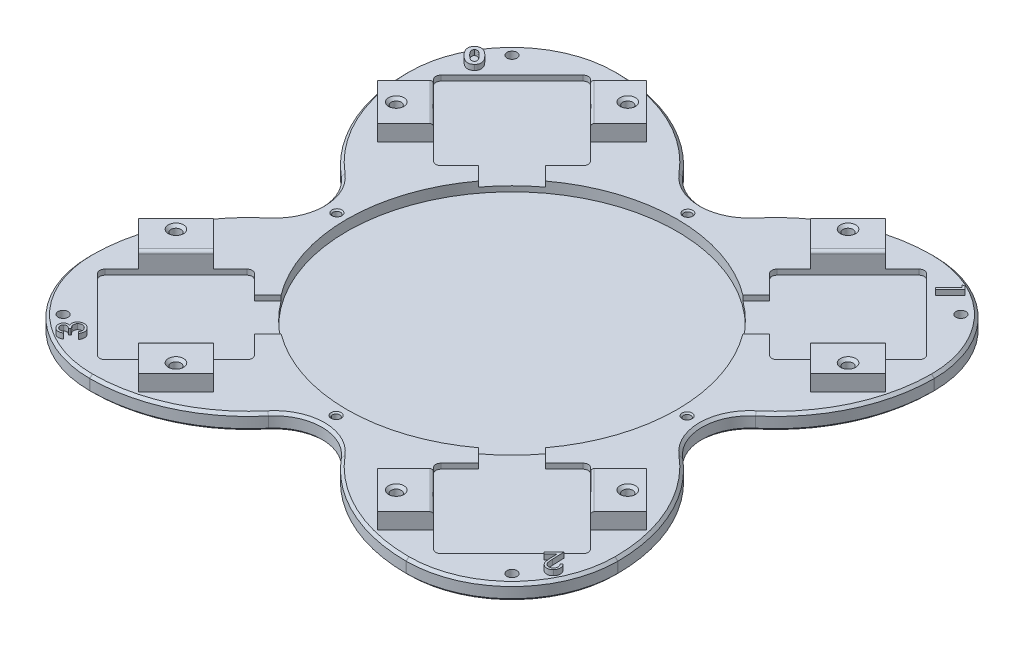
SolidWorks part; units mm, degrees
ref_plane "Спереди" through (0, 0, 0) normal (0, 0, 1) x (1, 0, 0)
ref_plane "Сверху" through (0, 0, 0) normal (0, 1, 0) x (1, 0, 0)
ref_plane "Справа" through (0, 0, 0) normal (1, 0, 0) x (0, 0, -1)
sketch "Эскиз1" plane through (0, 0, 0) normal (0, 1, 0) x (1, 0, 0)
  line L1 (-100, -100) -> (100, -100)
  line L2 (-100, -100) -> (-100, 100)
  line L3 (-100, 100) -> (100, 100)
  line L4 (100, -100) -> (100, 100)
  line L5 (0, 100) -> (0, -100) construction
  line L6 (-100, 0) -> (100, 0) construction
  line L11 (0, 75) -> (0, -75) construction
  line L12 (-39.5, 0) -> (39.5, 0) construction
  line L13 (-85, -85) -> (85, -85) construction
  line L14 (-85, -85) -> (-85, 85) construction
  line L15 (-85, 85) -> (85, 85) construction
  line L16 (85, -85) -> (85, 85) construction
  line L17 (0, 85) -> (0, -85) construction
  line L18 (-85, 0) -> (85, 0) construction
  circle A8 centre (-90, 0) radius 1.9
  circle A9 centre (0, 90) radius 1.9
  circle A10 centre (90, 0) radius 1.9
  circle A11 centre (0, -90) radius 1.9
  circle A12 centre (-85, 85) radius 1.9
  circle A13 centre (85, 85) radius 1.9
  circle A14 centre (85, -85) radius 1.9
  circle A15 centre (-85, -85) radius 1.9
  point P0 (0, 0)
  point P4 (0, 0)
  point P11 (0, 0)
  point P27 (0, 0)
  dimension "D6" = 90
  dimension "D2" = 3.8
  dimension "D1" = 200
  dimension "D8" = 170
  dimension "D7" = 4
extrude "Бобышка-Вытянуть1" add sketch "Эскиз1" along normal blind 6
sketch "Эскиз2" plane through (0, 6, 0) normal (0, 1, 0) x (1, 0, 0)
  line L0 (0, 72.2532) -> (0, 0) construction
  line L1 (0, 0) -> (100, 100) construction
  line L2 (63.6396, 33.9411) -> (33.9411, 63.6396)
  line L3 (63.6396, 33.9411) -> (93.3381, 63.6396)
  line L4 (33.9411, 63.6396) -> (63.6396, 93.3381)
  line L5 (93.3381, 63.6396) -> (63.6396, 93.3381)
  line L6 (63.6396, 33.9411) -> (63.6396, 93.3381) construction
  line L7 (33.9411, 63.6396) -> (93.3381, 63.6396) construction
  line L8 (33.9411, -63.6396) -> (63.6396, -33.9411)
  line L9 (33.9411, -63.6396) -> (63.6396, -93.3381)
  line L10 (63.6396, -93.3381) -> (93.3381, -63.6396)
  line L11 (63.6396, -33.9411) -> (93.3381, -63.6396)
  line L12 (-63.6396, -33.9411) -> (-33.9411, -63.6396)
  line L13 (-63.6396, -33.9411) -> (-93.3381, -63.6396)
  line L14 (-93.3381, -63.6396) -> (-63.6396, -93.3381)
  line L15 (-33.9411, -63.6396) -> (-63.6396, -93.3381)
  line L16 (-33.9411, 63.6396) -> (-63.6396, 33.9411)
  line L17 (-33.9411, 63.6396) -> (-63.6396, 93.3381)
  line L18 (-63.6396, 93.3381) -> (-93.3381, 63.6396)
  line L19 (-63.6396, 33.9411) -> (-93.3381, 63.6396)
  line L20 (0, 0) -> (119.0497, 0) construction
  point P6 (63.6396, 63.6396)
  point P24 (0, 0)
  dimension "D1" = 42
  dimension "D2" = 90
  dimension "D4" = 63.6396
  dimension "D5" = 63.6396
  dimension "D3" = 4
extrude "Вырез-Вытянуть1" cut sketch "Эскиз2" against normal blind 2
fillet "Скругление1" radius 2 16 edges at (63.6396, 5, -33.9411) (33.9411, 5, -63.6396) (93.3381, 5, -63.6396) (63.6396, 5, -93.3381) (-63.6396, 5, -93.3381) (-63.6396, 5, -33.9411) (-93.3381, 5, -63.6396) (-33.9411, 5, -63.6396) (63.6396, 5, 93.3381) (93.3381, 5, 63.6396) (63.6396, 5, 33.9411) (33.9411, 5, 63.6396) (-63.6396, 5, 93.3381) (-33.9411, 5, 63.6396) (-63.6396, 5, 33.9411) (-93.3381, 5, 63.6396)
sketch "Эскиз3" plane through (0, 6, 0) normal (0, 1, 0) x (1, 0, 0)
  line L0 (48.7904, 48.7904) -> (67.3817, 67.3817) construction
  line L1 (35.3553, 62.2254) -> (62.2254, 35.3553) construction
  line L2 (48.7904, 78.4889) -> (78.4889, 48.7904) construction
  line L3 (62.2254, 91.9239) -> (35.3553, 65.0538) construction
  line L4 (65.0538, 35.3553) -> (91.9239, 62.2254) construction
  line L5 (41.7193, 71.4178) -> (55.8614, 85.5599)
  line L6 (41.7193, 71.4178) -> (31.1127, 82.0244)
  line L7 (55.8614, 85.5599) -> (45.2548, 96.1665)
  line L8 (31.1127, 82.0244) -> (45.2548, 96.1665)
  line L9 (62.2254, 91.9239) -> (35.3553, 65.0538) construction
  line L10 (85.5599, 55.8614) -> (96.1665, 45.2548)
  line L11 (82.0244, 31.1127) -> (96.1665, 45.2548)
  line L12 (71.4178, 41.7193) -> (82.0244, 31.1127)
  line L13 (71.4178, 41.7193) -> (85.5599, 55.8614)
  line L44 (65.0538, 35.3553) -> (91.9239, 62.2254) construction
  line L45 (0, 128.3294) -> (0, 0) construction
  line L64 (0, 0) -> (145.1139, 0) construction
  line L65 (62.2254, 91.9239) -> (35.3553, 65.0538) construction
  line L90 (48.7904, -78.4889) -> (78.4889, -48.7904) construction
  line L91 (48.7904, -48.7904) -> (67.3817, -67.3817) construction
  line L92 (71.4178, -41.7193) -> (85.5599, -55.8614)
  line L93 (71.4178, -41.7193) -> (82.0244, -31.1127)
  line L94 (82.0244, -31.1127) -> (96.1665, -45.2548)
  line L95 (85.5599, -55.8614) -> (96.1665, -45.2548)
  line L96 (31.1127, -82.0244) -> (45.2548, -96.1665)
  line L97 (55.8614, -85.5599) -> (45.2548, -96.1665)
  line L98 (41.7193, -71.4178) -> (31.1127, -82.0244)
  line L99 (41.7193, -71.4178) -> (55.8614, -85.5599)
  line L100 (-48.7904, -48.7904) -> (-67.3817, -67.3817) construction
  line L101 (-48.7904, -78.4889) -> (-78.4889, -48.7904) construction
  line L102 (-48.7904, 78.4889) -> (-78.4889, 48.7904) construction
  line L103 (-48.7904, 48.7904) -> (-67.3817, 67.3817) construction
  line L104 (-41.7193, -71.4178) -> (-55.8614, -85.5599)
  line L105 (-41.7193, -71.4178) -> (-31.1127, -82.0244)
  line L106 (-55.8614, -85.5599) -> (-45.2548, -96.1665)
  line L107 (-31.1127, -82.0244) -> (-45.2548, -96.1665)
  line L108 (-85.5599, -55.8614) -> (-96.1665, -45.2548)
  line L109 (-82.0244, -31.1127) -> (-96.1665, -45.2548)
  line L110 (-71.4178, -41.7193) -> (-82.0244, -31.1127)
  line L111 (-71.4178, -41.7193) -> (-85.5599, -55.8614)
  line L112 (-71.4178, 41.7193) -> (-85.5599, 55.8614)
  line L113 (-71.4178, 41.7193) -> (-82.0244, 31.1127)
  line L114 (-82.0244, 31.1127) -> (-96.1665, 45.2548)
  line L115 (-85.5599, 55.8614) -> (-96.1665, 45.2548)
  line L116 (-31.1127, 82.0244) -> (-45.2548, 96.1665)
  line L117 (-55.8614, 85.5599) -> (-45.2548, 96.1665)
  line L118 (-41.7193, 71.4178) -> (-31.1127, 82.0244)
  line L119 (-41.7193, 71.4178) -> (-55.8614, 85.5599)
  point P16 (48.7904, 78.4889)
  dimension "D1" = 20
  dimension "D2" = 15
extrude "Бобышка-Вытянуть3" add sketch "Эскиз3" along normal blind 6
fillet "Скругление4" radius 40 4 edges at (100, 3, -100) (100, 3, 100) (-100, 3, 100) (-100, 3, -100)
sketch "Эскиз4" plane through (0, 12, 0) normal (0, 1, 0) x (1, 0, 0)
  line L0 (89.0955, 38.1838) -> (38.1838, 89.0955) construction
  line L1 (82.0244, 31.1127) -> (96.1665, 45.2548) construction
  line L2 (45.2548, 96.1665) -> (31.1127, 82.0244) construction
  line L3 (41.7193, 71.4178) -> (55.8614, 85.5599) construction
  line L4 (48.7904, 48.7904) -> (78.4889, 78.4889) construction
  line L5 (35.3553, 62.2254) -> (62.2254, 35.3553) construction
  line L6 (91.9239, 65.0538) -> (65.0538, 91.9239) construction
  line L7 (0, 119.2498) -> (0, 0) construction
  line L8 (0, 0) -> (156.895, 0) construction
  line L9 (48.7904, -48.7904) -> (78.4889, -78.4889) construction
  line L10 (89.0955, -38.1838) -> (38.1838, -89.0955) construction
  line L11 (-89.0955, -38.1838) -> (-38.1838, -89.0955) construction
  line L12 (-48.7904, -48.7904) -> (-78.4889, -78.4889) construction
  line L13 (-48.7904, 48.7904) -> (-78.4889, 78.4889) construction
  line L14 (-89.0955, 38.1838) -> (-38.1838, 89.0955) construction
  circle A0 centre (41.7193, 85.5599) radius 1.9
  circle A1 centre (85.5599, 41.7193) radius 1.9
  circle A14 centre (85.5599, -41.7193) radius 1.9
  circle A15 centre (41.7193, -85.5599) radius 1.9
  circle A16 centre (-41.7193, -85.5599) radius 1.9
  circle A17 centre (-85.5599, -41.7193) radius 1.9
  circle A18 centre (-85.5599, 41.7193) radius 1.9
  circle A19 centre (-41.7193, 85.5599) radius 1.9
  dimension "D1" = 10
  dimension "D3" = 62
  dimension "D2" = 3.8
  dimension "D4" = 31
extrude "Вырез-Вытянуть2" cut sketch "Эскиз4" against normal blind 8
sketch "Эскиз8" plane through (0, 6, 0) normal (0, 1, 0) x (1, 0, 0)
  line L0 (48.7904, 48.7904) -> (72.3205, 72.3205) construction
  line L1 (35.3553, 62.2254) -> (62.2254, 35.3553) construction
  line L2 (44.5477, 31.8198) -> (31.8198, 44.5477)
  line L3 (44.5477, 31.8198) -> (65.7609, 53.033)
  line L4 (31.8198, 44.5477) -> (53.033, 65.7609)
  line L5 (65.7609, 53.033) -> (53.033, 65.7609)
  line L6 (44.5477, 31.8198) -> (53.033, 65.7609) construction
  line L7 (31.8198, 44.5477) -> (65.7609, 53.033) construction
  line L20 (0, 107.5006) -> (0, 0) construction
  line L21 (0, 0) -> (140.6034, 0) construction
  line L22 (31.8198, -44.5477) -> (65.7609, -53.033) construction
  line L23 (44.5477, -31.8198) -> (53.033, -65.7609) construction
  line L24 (48.7904, -48.7904) -> (72.3205, -72.3205) construction
  line L25 (65.7609, -53.033) -> (53.033, -65.7609)
  line L26 (31.8198, -44.5477) -> (53.033, -65.7609)
  line L27 (44.5477, -31.8198) -> (65.7609, -53.033)
  line L28 (44.5477, -31.8198) -> (31.8198, -44.5477)
  line L29 (-48.7904, -48.7904) -> (-72.3205, -72.3205) construction
  line L30 (-44.5477, -31.8198) -> (-53.033, -65.7609) construction
  line L31 (-31.8198, -44.5477) -> (-65.7609, -53.033) construction
  line L32 (-31.8198, 44.5477) -> (-65.7609, 53.033) construction
  line L33 (-44.5477, 31.8198) -> (-53.033, 65.7609) construction
  line L34 (-48.7904, 48.7904) -> (-72.3205, 72.3205) construction
  line L35 (-44.5477, -31.8198) -> (-31.8198, -44.5477)
  line L36 (-44.5477, -31.8198) -> (-65.7609, -53.033)
  line L37 (-31.8198, -44.5477) -> (-53.033, -65.7609)
  line L38 (-65.7609, -53.033) -> (-53.033, -65.7609)
  line L39 (-65.7609, 53.033) -> (-53.033, 65.7609)
  line L40 (-31.8198, 44.5477) -> (-53.033, 65.7609)
  line L41 (-44.5477, 31.8198) -> (-65.7609, 53.033)
  line L42 (-44.5477, 31.8198) -> (-31.8198, 44.5477)
  point P24 (0, 16.9706)
  dimension "D1" = 18
  dimension "D2" = 30
extrude "Вырез-Вытянуть4" cut sketch "Эскиз8" against normal blind 2 contours L2 L3 L5 L4
fillet "Скругление6" radius 1 8 edges at (78.4889, 12, -48.7904) (48.7904, 12, -78.4889) (-78.4889, 12, 48.7904) (-48.7904, 12, 78.4889) (48.7904, 12, 78.4889) (78.4889, 12, 48.7904) (-78.4889, 12, -48.7904) (-48.7904, 12, -78.4889)
sketch "Эскиз9" plane through (0, 6, 0) normal (0, 1, 0) x (1, 0, 0)
  line L0 (-70.7105, 0.151) -> (0.151, 70.7105) construction
  line L1 (-70.7105, 0.151) -> (-0.151, -70.7105) construction
  line L2 (0.151, 70.7105) -> (70.7105, -0.151) construction
  line L3 (-0.151, -70.7105) -> (70.7105, -0.151) construction
  line L4 (-70.7105, 0.151) -> (70.7105, -0.151) construction
  line L5 (0.151, 70.7105) -> (-0.151, -70.7105) construction
  line L6 (0, 0) -> (60.8554, 60.8554) construction
  circle A0 centre (0.1419, 66.4679) radius 1.4
  circle A4 centre (-0.1419, -66.4679) radius 1.4
  circle A5 centre (66.4679, -0.1419) radius 1.4
  circle A6 centre (-66.4679, 0.1419) radius 1.4
  point P1 (0, 0)
  dimension "D2" = 2.8
  dimension "D3" = 3
  dimension "D4" = 3
  dimension "D5" = 94
  dimension "D1" = 100
extrude "Вырез-Вытянуть5" cut sketch "Эскиз9" against normal blind 10
sketch "Эскиз10" plane through (0, 6, 0) normal (0, 1, 0) x (1, 0, 0)
  line L0 (-89.4334, 70.8427) -> (-83.9454, 76.3307) construction
  line L1 (0, 108.5259) -> (0, 0) construction
  line L2 (71.3984, 88.9173) -> (76.8147, 83.501) construction
  line L3 (90.0364, -69.9365) -> (84.274, -75.6989) construction
  line L4 (-72.0522, -89.0668) -> (-79.6906, -81.6618) construction
  text T0 "<b>0</b>\r\n" font "Century Gothic" height 8
  text T1 "1\r\n" font "Century Gothic" height 8
  text T2 "2" font "Century Gothic" height 8
  text T3 "3\r\n" font "Century Gothic" height 8
extrude "Бобышка-Вытянуть6" add sketch "Эскиз10" along normal blind 2
sketch "Эскиз11" plane through (0, 6, 0) normal (0, 1, 0) x (1, 0, 0)
  circle A0 centre (0, 0) radius 62.5
  dimension "D1" = 125
extrude "Вырез-Вытянуть6" cut sketch "Эскиз11" against normal blind 4 and the other way through all
chamfer "Фаска2" distance 1 angle 45 8 edges at (-85.5599, 12, 39.8193) (-41.7193, 12, 87.4599) (41.7193, 12, 83.6599) (85.5599, 12, 43.6193) (85.5599, 12, -43.6193) (41.7193, 12, -83.6599) (-85.5599, 12, -39.8193) (-41.7193, 12, -87.4599)
chamfer "Фаска3" distance 0.5 angle 45 4 edges at (-66.4679, 6, -1.5419) (-0.1419, 6, 65.0679) (66.4679, 6, 1.5419) (0.1419, 6, -65.0679)
sketch "Эскиз12" plane through (0, 6, 0) normal (0, 1, 0) x (1, 0, 0)
  circle A0 centre (90, 0) radius 18
  circle A1 centre (0, -90) radius 18
  circle A2 centre (-90, 0) radius 18
  circle A3 centre (0, 90) radius 18
  point P12 (0, 0)
  dimension "D1" = 36
  dimension "D2" = 4
extrude "Вырез-Вытянуть7" cut sketch "Эскиз12" against normal through all contours A0
fillet "Скругление7" radius 60 8 edges at (100, 3, -14.9666) (100, 3, 14.9666) (14.9666, 3, 100) (-14.9666, 3, 100) (-100, 3, 14.9666) (-100, 3, -14.9666) (-14.9666, 3, -100) (14.9666, 3, -100)
chamfer "Фаска4" distance 1 angle 45 32 edges at (-85, 0, 86.9) (85, 0, -83.1) (-85, 0, -83.1) (85, 0, 86.9) (-66.4679, 0, -1.5419) (66.4679, 0, -1.2581) (-0.1419, 0, 65.0679) (0.1419, 0, -67.8679) (34.447, 0, 94.3493) (59.9333, 0, 100) (88.2843, 0, 88.2843) (100, 0, 59.9333) (94.3493, 0, 34.447) (72, 0, 0) (94.3493, 0, -34.447) (100, 0, -59.9333) (88.2843, 0, -88.2843) (59.9333, 0, -100) (34.447, 0, -94.3493) (0, 0, -72) (-34.447, 0, -94.3493) (-59.9333, 0, -100) (-88.2843, 0, -88.2843) (-100, 0, -59.9333) (-94.3493, 0, -34.447) (-72, 0, 0) (-94.3493, 0, 34.447) (-100, 0, 59.9333) (-88.2843, 0, 88.2843) (-59.9333, 0, 100) (-34.447, 0, 94.3493) (0, 0, 72)
chamfer "Фаска5" distance 1 angle 45 24 edges at (-72, 6, 0) (-94.3493, 6, -34.447) (-94.3493, 6, 34.447) (-100, 6, -59.9333) (-100, 6, 59.9333) (-88.2843, 6, -88.2843) (-88.2843, 6, 88.2843) (-59.9333, 6, -100) (-59.9333, 6, 100) (-34.447, 6, -94.3493) (-34.447, 6, 94.3493) (0, 6, -72) (0, 6, 72) (34.447, 6, -94.3493) (34.447, 6, 94.3493) (59.9333, 6, -100) (59.9333, 6, 100) (88.2843, 6, -88.2843) (88.2843, 6, 88.2843) (100, 6, -59.9333) (100, 6, 59.9333) (94.3493, 6, -34.447) (94.3493, 6, 34.447) (72, 6, 0)
